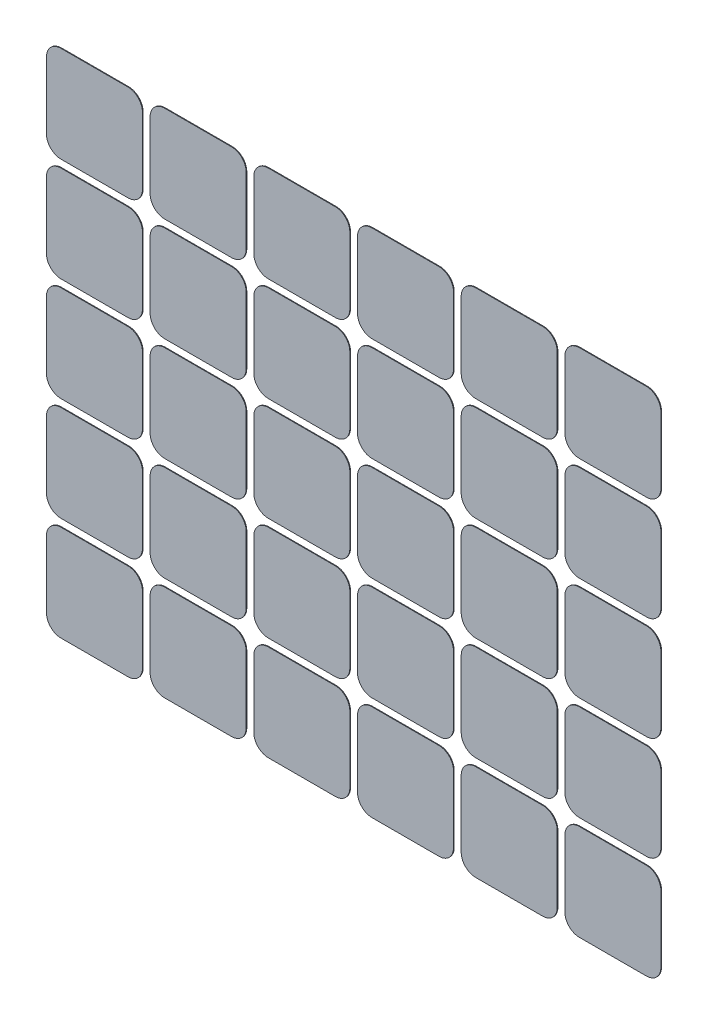
SolidWorks part; units mm, degrees
ref_plane "Ebene vorne" through (0, 0, 0) normal (0, 0, 1) x (1, 0, 0)
ref_plane "Ebene oben" through (0, 0, 0) normal (0, 1, 0) x (1, 0, 0)
ref_plane "Ebene rechts" through (0, 0, 0) normal (1, 0, 0) x (0, 0, -1)
sketch "Skizze1" plane through (0, 0, 0) normal (0, 0, 1) x (1, 0, 0)
  line L0 (-14.35, 10) -> (-14.35, -10)
  line L1 (10, 15) -> (-10, 15)
  line L2 (15, 10) -> (15, -10)
  line L3 (10, -15) -> (-10, -15)
  line L4 (-15, 10) -> (-15, -10)
  line L5 (15, 15) -> (-15, -15) construction
  line L6 (15, -15) -> (-15, 15) construction
  line L7 (10, -14.35) -> (-10, -14.35)
  line L8 (14.35, 10) -> (14.35, -10)
  line L9 (10, 14.35) -> (-10, 14.35)
  arc A0 (-10, -15) -> (-15, -10) centre (-10, -10) cw
  arc A1 (15, -10) -> (10, -15) centre (10, -10) cw
  arc A2 (10, 15) -> (15, 10) centre (10, 10) cw
  arc A3 (-10, 15) -> (-15, 10) centre (-10, 10) ccw
  arc A4 (-10, -14.35) -> (-14.35, -10) centre (-10, -10) cw
  arc A5 (14.35, -10) -> (10, -14.35) centre (10, -10) cw
  arc A6 (10, 14.35) -> (14.35, 10) centre (10, 10) cw
  arc A7 (-10, 14.35) -> (-14.35, 10) centre (-10, 10) ccw
  point P0 (0, 0)
  dimension "D3" = 5
  dimension "D1" = 30
  dimension "D2" = 30
  dimension "D4" = 0.65
extrude "Aufsatz-Linear austragen1" add sketch "Skizze1" along normal blind 0.2 contours L9 A7 L0 A4 L7 A5 L8 A6
pattern_linear "Lineares Muster1" count 6 spacing 31 along (1, 0, 0) count 5 spacing 31 along (0, 1, 0) of "Aufsatz-Linear austragen1"
